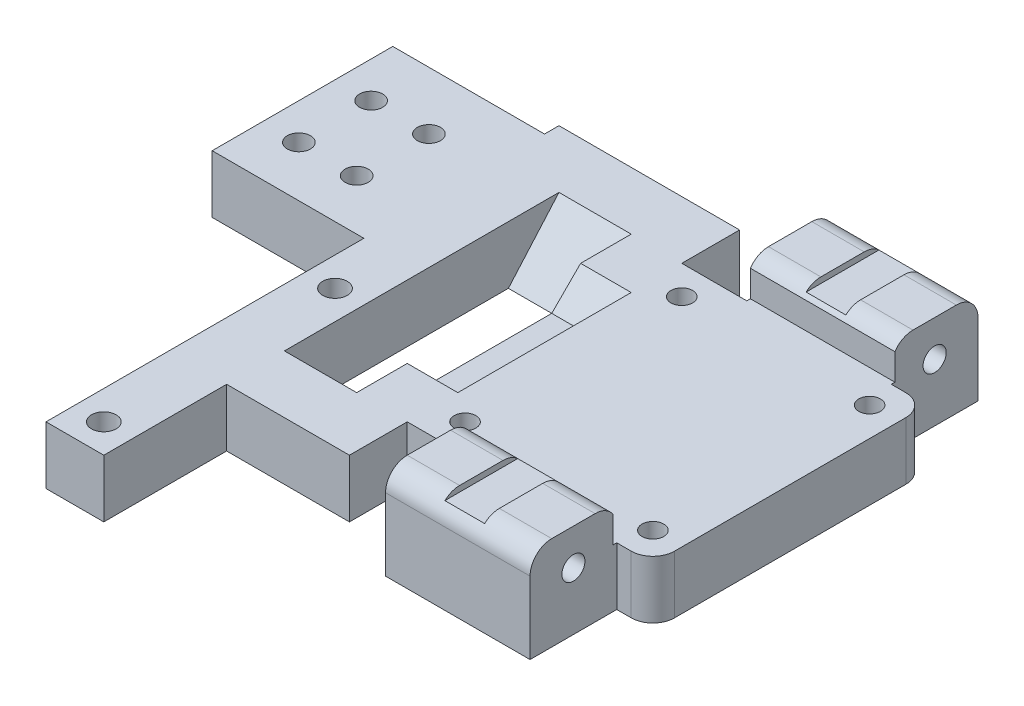
SolidWorks part; units mm, degrees
ref_plane "Front" through (0, 0, 0) normal (0, 0, 1) x (1, 0, 0)
ref_plane "Top" through (0, 0, 0) normal (0, 1, 0) x (1, 0, 0)
ref_plane "Right" through (0, 0, 0) normal (1, 0, 0) x (0, 0, -1)
sketch "Sketch1" plane through (0, 0, 0) normal (0, 1, 0) x (1, 0, 0)
  line L1 (0, 0) -> (300, 0)
  line L2 (0, 0) -> (0, -20)
  line L3 (0, -20) -> (300, -20)
  line L4 (300, 0) -> (300, -20)
  dimension "D1" = 20
  dimension "D2" = 300
extrude "Boss-Extrude1" add sketch "Sketch1" along normal blind 8
sketch "Sketch2" plane through (0, 0, 20) normal (0, 0, 1) x (1, 0, 0)
  line L0 (0, 8) -> (300, 8) construction
  line L1 (0, 0) -> (34, 0)
  line L2 (0, 0) -> (0, 8)
  line L3 (0, 8) -> (34, 8)
  line L4 (34, 0) -> (34, 8)
  line L5 (266, 8) -> (300, 8)
  line L6 (300, 0) -> (300, 8)
  line L7 (266, 0) -> (300, 0)
  line L8 (266, 0) -> (266, 8)
  dimension "D1" = 34
  dimension "D2" = 2
extrude "Boss-Extrude2" add sketch "Sketch2" along normal blind 9
sketch "Sketch3" plane through (0, 0, 0) normal (0, 0, -1) x (-1, 0, 0)
  line L0 (-300, 8) -> (0, 8) construction
  line L1 (0, 0) -> (-34, 0)
  line L2 (0, 0) -> (0, 8)
  line L3 (0, 8) -> (-34, 8)
  line L4 (-34, 0) -> (-34, 8)
  line L5 (-300, 0) -> (-300, 8)
  line L6 (-266, 8) -> (-300, 8)
  line L7 (-266, 0) -> (-266, 8)
  line L8 (-266, 0) -> (-300, 0)
  dimension "D1" = 34
  dimension "D2" = 2
extrude "Boss-Extrude3" add sketch "Sketch3" along normal blind 9
sketch "Sketch4" plane through (0, 8, 0) normal (0, 1, 0) x (1, 0, 0)
  line L0 (0, 9) -> (34, 9) construction
  line L1 (0, 9) -> (0, -29) construction
  circle A0 centre (4, 5) radius 1.5
  circle A1 centre (30, 5) radius 1.5
  circle A2 centre (30, -25) radius 1.5
  circle A3 centre (4, -25) radius 1.5
  circle A4 centre (296, -25) radius 1.5
  circle A5 centre (296, 5) radius 1.5
  circle A6 centre (270, -25) radius 1.5
  circle A7 centre (270, 5) radius 1.5
  dimension "D1" = 3
  dimension "D2" = 4
  dimension "D3" = 4
  dimension "D4" = 2
  dimension "D5" = 2
  dimension "D6" = 2
extrude "Cut-Extrude1" cut sketch "Sketch4" against normal through all
sketch "Sketch5" plane through (0, 0, 20) normal (0, 0, 1) x (1, 0, 0)
  line L0 (34, 8) -> (266, 8) construction
  line L1 (266, 0) -> (241, 0)
  line L2 (266, 0) -> (266, 8)
  line L3 (266, 8) -> (241, 8)
  line L4 (241, 0) -> (241, 8)
  dimension "D1" = 25
extrude "Boss-Extrude4" add sketch "Sketch5" along normal blind 17
sketch "Sketch6" plane through (0, 0, 0) normal (0, 0, -1) x (-1, 0, 0)
  line L0 (-266, 0) -> (-34, 0) construction
  line L1 (-266, 8) -> (-241, 8)
  line L2 (-266, 8) -> (-266, 0)
  line L3 (-266, 0) -> (-241, 0)
  line L4 (-241, 8) -> (-241, 0)
  dimension "D1" = 25
extrude "Boss-Extrude5" add sketch "Sketch6" along normal blind 17
sketch "Sketch7" plane through (0, 8, 0) normal (0, 1, 0) x (1, 0, 0)
  line L0 (266, -37) -> (241, -37) construction
  line L1 (259, -29) -> (249, -29)
  line L2 (259, -29) -> (259, 9)
  line L3 (259, 9) -> (249, 9)
  line L4 (249, -29) -> (249, 9)
  line L5 (241, -37) -> (241, -20) construction
  dimension "D1" = 10
  dimension "D2" = 38
  dimension "D3" = 8
  dimension "D4" = 8
extrude "Cut-Extrude2" cut sketch "Sketch7" against normal through all
sketch "Sketch8" plane through (0, 8, 0) normal (0, 1, 0) x (1, 0, 0)
  line L0 (259, -29) -> (259, 9) construction
  line L1 (259, -18) -> (266, -18)
  line L2 (259, -18) -> (259, -2)
  line L3 (259, -2) -> (266, -2)
  line L4 (266, -18) -> (266, -2)
  line L5 (266, -37) -> (241, -37) construction
  dimension "D1" = 7
  dimension "D2" = 16
  dimension "D3" = 19
extrude "Cut-Extrude3" cut sketch "Sketch8" against normal blind 4
sketch "Sketch9" plane through (259, 0, 0) normal (-1, 0, 0) x (0, 0, 1)
  line L0 (18, 4) -> (22, 8)
  line L1 (29, 8) -> (18, 8) construction
  line L2 (22, 8) -> (18, 8)
  line L3 (18, 8) -> (18, 4)
  line L4 (2, 4) -> (-2, 8)
  line L5 (2, 8) -> (-9, 8) construction
  line L6 (-2, 8) -> (2, 8)
  line L7 (2, 8) -> (2, 4)
  dimension "D1" = 4
  dimension "D2" = 4
extrude "Cut-Extrude4" cut sketch "Sketch9" against normal blind 7
sketch "Sketch10" plane through (259, 0, 0) normal (-1, 0, 0) x (0, 0, 1)
  line L0 (-9, 8) -> (-2, 0)
  line L1 (29, 0) -> (-9, 0) construction
  line L2 (-2, 0) -> (-9, 0)
  line L3 (-9, 0) -> (-9, 8)
  line L4 (29, 8) -> (22, 0)
  line L5 (22, 0) -> (29, 0)
  line L6 (29, 0) -> (29, 8)
  line L7 (-51.4523, 12.1971) -> (-51.8778, 12.5861)
  line M6 (-9, 8) -> (-9, 0)
  line M7 (-9, 0) -> (29, 0)
  line M8 (29, 0) -> (29, 8)
  dimension "D1" = 7
  dimension "D2" = 7
extrude "Boss-Extrude6" add sketch "Sketch10" along normal blind 10 contours L0 M6 M7 | L4 M8 M7
sketch "Sketch12" plane through (0, 0, 37) normal (0, 0, 1) x (1, 0, 0)
  line L0 (241, 0) -> (266, 0) construction
  line L1 (241, 8) -> (249, 8)
  line L2 (241, 8) -> (241, 0)
  line L3 (241, 0) -> (249, 0)
  line L4 (249, 8) -> (249, 0)
  dimension "D1" = 8
extrude "Boss-Extrude7" add sketch "Sketch12" along normal blind 17
sketch "Sketch13" plane through (0, 8, 0) normal (0, 1, 0) x (1, 0, 0)
  line L0 (249, -54) -> (241, -54) construction
  line L1 (249, -54) -> (249, -37) construction
  circle A0 centre (245, -50) radius 1.7
  circle A1 centre (245, -18) radius 1.7
  dimension "D1" = 3.4
  dimension "D2" = 4
  dimension "D3" = 4
  dimension "D4" = 2
extrude "Cut-Extrude6" cut sketch "Sketch13" against normal through all
sketch "Sketch14" plane through (0, 0, 29) normal (0, 0, 1) x (1, 0, 0)
  line L1 (295, 13) -> (275, 13)
  line L2 (295, 13) -> (295, 0)
  line L3 (295, 0) -> (275, 0)
  line L4 (275, 13) -> (275, 0)
  line L5 (266, 0) -> (300, 0) construction
  line L7 (266, 8) -> (266, 0) construction
  dimension "D1" = 20
  dimension "D2" = 9
  dimension "D3" = 13
extrude "Boss-Extrude8" add sketch "Sketch14" along normal blind 12
sketch "Sketch15" plane through (295, 0, 0) normal (1, 0, 0) x (0, 0, -1)
  line L0 (-41, 0) -> (-41, 13) construction
  line L1 (-41, 13) -> (-29, 13) construction
  circle A0 centre (-35, 8) radius 1.6
  dimension "D1" = 3.2
  dimension "D2" = 6
  dimension "D3" = 5
extrude "Cut-Extrude7" cut sketch "Sketch15" against normal blind 20
sketch "Sketch16" plane through (0, 0, -9) normal (0, 0, -1) x (-1, 0, 0)
  line L1 (-295, 13) -> (-275, 13)
  line L2 (-295, 13) -> (-295, 0)
  line L3 (-295, 0) -> (-275, 0)
  line L4 (-275, 13) -> (-275, 0)
  line L5 (-300, 0) -> (-266, 0) construction
  line L6 (-266, 0) -> (-266, 8) construction
  dimension "D1" = 20
  dimension "D2" = 9
  dimension "D3" = 13
extrude "Boss-Extrude9" add sketch "Sketch16" along normal blind 12
sketch "Sketch17" plane through (295, 0, 0) normal (1, 0, 0) x (0, 0, -1)
  line L1 (21, 13) -> (21, 0) construction
  line L2 (21, 13) -> (9, 13) construction
  circle A0 centre (15, 8) radius 1.6
  dimension "D1" = 3.2
  dimension "D2" = 5
  dimension "D3" = 6
extrude "Cut-Extrude8" cut sketch "Sketch17" against normal blind 20
sketch "Sketch18" plane through (0, 0, -9) normal (0, 0, -1) x (-1, 0, 0)
  line L1 (-25, 13) -> (-5, 13)
  line L2 (-25, 13) -> (-25, 0)
  line L3 (-25, 0) -> (-5, 0)
  line L4 (-5, 13) -> (-5, 0)
  line L5 (-34, 0) -> (0, 0) construction
  line L6 (-34, 8) -> (-34, 0) construction
  dimension "D1" = 20
  dimension "D2" = 9
  dimension "D3" = 13
extrude "Boss-Extrude10" add sketch "Sketch18" along normal blind 12
sketch "Sketch19" plane through (5, 0, 0) normal (-1, 0, 0) x (0, 0, 1)
  line L0 (-21, 0) -> (-21, 13) construction
  line L1 (-21, 13) -> (-9, 13) construction
  circle A0 centre (-15, 8) radius 1.6
  dimension "D1" = 3.2
  dimension "D2" = 6
  dimension "D3" = 5
extrude "Cut-Extrude9" cut sketch "Sketch19" against normal blind 20
sketch "Sketch20" plane through (0, 0, 29) normal (0, 0, 1) x (1, 0, 0)
  line L1 (5, 13) -> (25, 13)
  line L2 (5, 13) -> (5, 0)
  line L3 (5, 0) -> (25, 0)
  line L4 (25, 13) -> (25, 0)
  line L5 (0, 0) -> (34, 0) construction
  line L6 (34, 0) -> (34, 8) construction
  dimension "D1" = 20
  dimension "D2" = 9
  dimension "D3" = 13
extrude "Boss-Extrude11" add sketch "Sketch20" along normal blind 12
sketch "Sketch21" plane through (5, 0, 0) normal (-1, 0, 0) x (0, 0, 1)
  line L0 (41, 13) -> (41, 0) construction
  line L2 (41, 13) -> (29, 13) construction
  circle A0 centre (35, 8) radius 1.6
  dimension "D1" = 3.2
  dimension "D2" = 6
  dimension "D3" = 5
extrude "Cut-Extrude10" cut sketch "Sketch21" against normal blind 20
fillet "Fillet6" radius 3 8 edges at (15, 13, 41) (15, 13, 29) (15, 13, -9) (15, 13, -21) (285, 13, 41) (285, 13, 29) (285, 13, -9) (285, 13, -21)
sketch "Sketch28" plane through (0, 0, 0) normal (-1, 0, 0) x (0, 0, 1)
  line L1 (78.9453, 217.6934) -> (-119.9362, 217.6934)
  line L2 (78.9453, 217.6934) -> (78.9453, -338.6618)
  line L3 (78.9453, -338.6618) -> (-119.9362, -338.6618)
  line L4 (-119.9362, 217.6934) -> (-119.9362, -338.6618)
extrude "Cut-Extrude14" cut sketch "Sketch28" against normal blind 220
sketch "Sketch29" plane through (0, 0, 0) normal (0, 0, -1) x (-1, 0, 0)
  line L1 (-241, 0) -> (-220, 0)
  line L2 (-241, 0) -> (-241, 8)
  line L3 (-241, 8) -> (-220, 8)
  line L4 (-220, 0) -> (-220, 8)
extrude "Boss-Extrude12" add sketch "Sketch29" along normal blind 15
sketch "Sketch30" plane through (0, 0, 0) normal (0, -1, 0) x (-1, 0, 0)
  line L1 (-220, -20) -> (-241, -20)
  line L2 (-220, -20) -> (-220, -10)
  line L3 (-220, -10) -> (-241, -10)
  line L4 (-241, -20) -> (-241, -10)
  dimension "D1" = 21
  dimension "D2" = 10
extrude "Cut-Extrude15" cut sketch "Sketch30" against normal through all
sketch "Sketch31" plane through (0, 0, 0) normal (0, -1, 0) x (-1, 0, 0)
  line L0 (-220, -10) -> (-220, 15) construction
  line L1 (-241, 15) -> (-220, 15) construction
  line L2 (-220, -10) -> (-241, -10) construction
  circle A0 centre (-225, 7) radius 1.6
  circle A1 centre (-225, -3) radius 1.6
  circle A2 centre (-233, 7) radius 1.6
  circle A3 centre (-233, -3) radius 1.6
  dimension "D1" = 3.2
  dimension "D2" = 3.2
  dimension "D3" = 3.2
  dimension "D4" = 3.2
  dimension "D5" = 5
  dimension "D6" = 8
  dimension "D7" = 5
  dimension "D8" = 7
  dimension "D9" = 8
  dimension "D10" = 8
  dimension "D11" = 7
  dimension "D12" = 8
extrude "Cut-Extrude16" cut sketch "Sketch31" against normal through all
fillet "Fillet7" radius 3 2 edges at (300, 4, -9) (300, 4, 29)
sketch "Sketch32" plane through (0, 13, 0) normal (0, 1, 0) x (1, 0, 0)
  line L0 (295, -38) -> (295, -32) construction
  line L1 (287.75, -42.4531) -> (282.25, -42.4531)
  line L2 (287.75, -42.4531) -> (287.75, 28.0104)
  line L3 (287.75, 28.0104) -> (282.25, 28.0104)
  line L4 (282.25, -42.4531) -> (282.25, 28.0104)
  dimension "D1" = 5.5
  dimension "D2" = 7.25
extrude "Cut-Extrude17" cut sketch "Sketch32" against normal blind 0.8
sketch "Sketch33" plane through (0, 0, 29) normal (0, 0, -1) x (-1, 0, 0)
  line L1 (-275, 8) -> (-295, 8)
  line L2 (-275, 8) -> (-275, 12.9638)
  line L3 (-275, 12.9638) -> (-295, 12.9638)
  line L4 (-295, 8) -> (-295, 12.9638)
  dimension "D1" = 20
extrude "Cut-Extrude18" cut sketch "Sketch33" against normal blind 0.5
sketch "Sketch34" plane through (0, 0, -9) normal (0, 0, 1) x (1, 0, 0)
  line L1 (275, 8) -> (295, 8)
  line L2 (275, 8) -> (275, 19.9424)
  line L3 (275, 19.9424) -> (295, 19.9424)
  line L4 (295, 8) -> (295, 19.9424)
  dimension "D1" = 20
extrude "Cut-Extrude19" cut sketch "Sketch34" against normal blind 0.5
